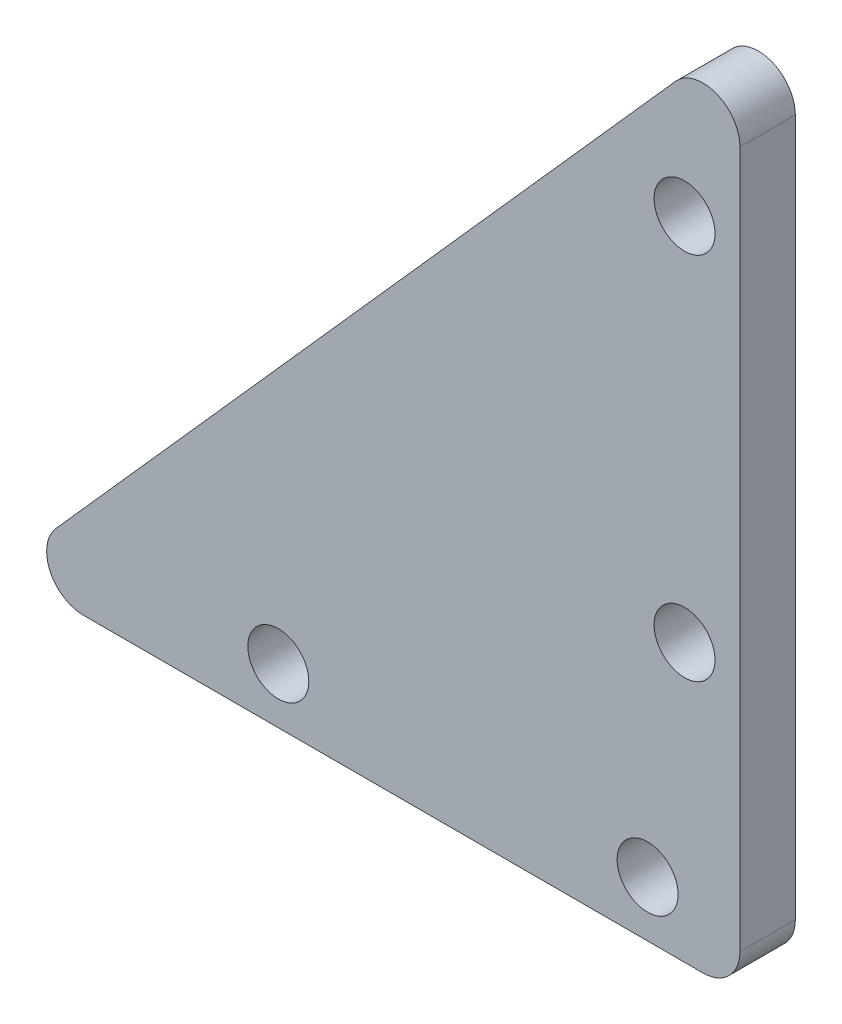
SolidWorks part; units mm, degrees
material "玻纤板"
ref_plane "前视基准面" through (0, 0, 0) normal (0, 0, 1) x (1, 0, 0)
ref_plane "上视基准面" through (0, 0, 0) normal (0, 1, 0) x (1, 0, 0)
ref_plane "右视基准面" through (0, 0, 0) normal (1, 0, 0) x (0, 0, -1)
other "Configuration Table"
sketch "草图1" plane through (0, 0, 0) normal (0, 0, 1) x (1, 0, 0)
  line L0 (0, 0) -> (-40, 0)
  line L1 (-40, 0) -> (0, 45)
  line L2 (0, 45) -> (0, 0)
  dimension "D1" = 45
  dimension "D2" = 40
extrude "凸台-拉伸1" add sketch "草图1" along normal blind 3
sketch "草图2" plane through (0, 0, 3) normal (0, 0, 1) x (1, 0, 0)
  line L0 (0, 0) -> (0, 45) construction
  line L1 (-40, 0) -> (0, 0) construction
  circle A0 centre (-5, 3) radius 1.65
  circle A1 centre (-25, 3) radius 1.65
  point P8 (0, 0)
  dimension "D1" = 5
  dimension "D2" = 3
  dimension "D3" = 3.3
  dimension "D4" = 20
extrude "切除-拉伸1" cut sketch "草图2" against normal blind 3
sketch "草图3" plane through (0, 0, 3) normal (0, 0, 1) x (1, 0, 0)
  line L0 (-40, 0) -> (0, 0) construction
  line L1 (0, 0) -> (0, 45) construction
  circle A0 centre (-3, 15) radius 1.65
  circle A1 centre (-3, 35) radius 1.65
  point P8 (0, 0)
  dimension "D1" = 15
  dimension "D3" = 20
  dimension "D4" = 3.3
  dimension "D2" = 3
extrude "切除-拉伸2" cut sketch "草图3" against normal blind 3
fillet "圆角1" radius 2 3 edges at (0, 0, 1.5) (-40, 0, 1.5) (0, 45, 1.5)
